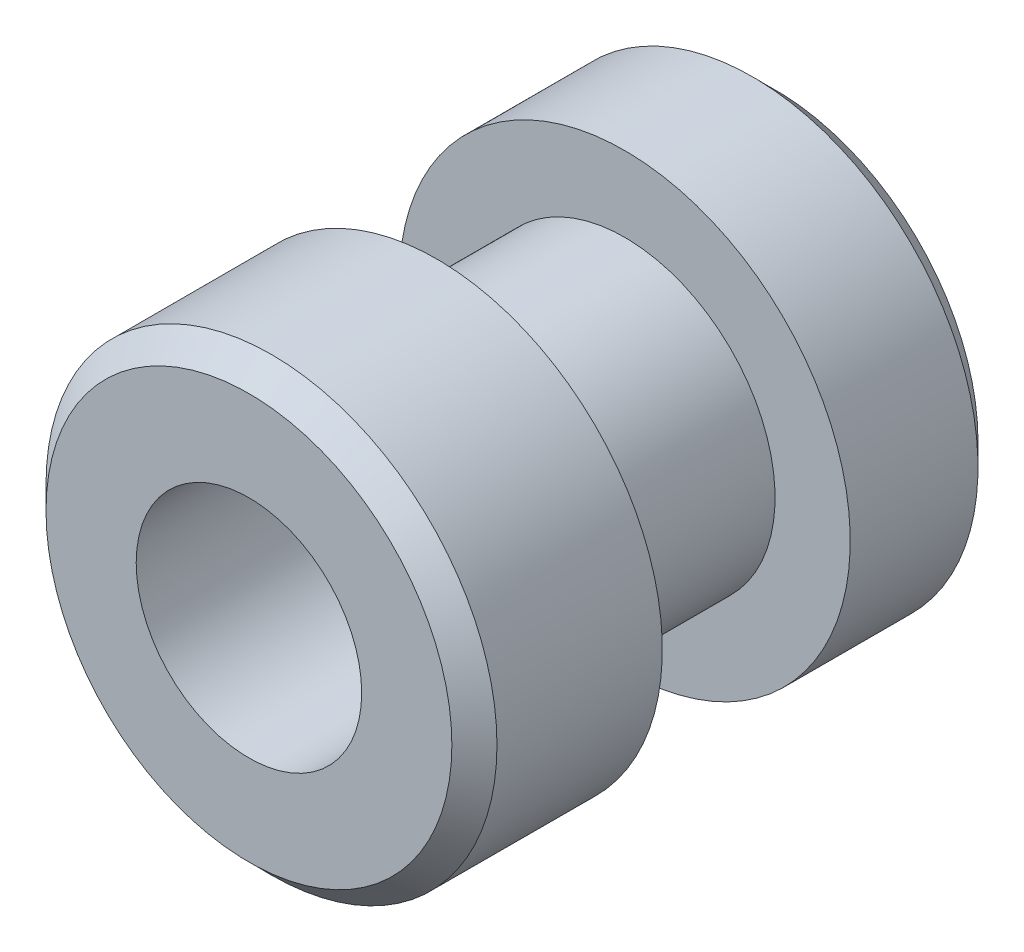
SolidWorks part; units mm, degrees
material "硅橡胶"
ref_plane "前视基准面" through (0, 0, 0) normal (0, 0, 1) x (1, 0, 0)
ref_plane "上视基准面" through (0, 0, 0) normal (0, 1, 0) x (1, 0, 0)
ref_plane "右视基准面" through (0, 0, 0) normal (1, 0, 0) x (0, 0, -1)
sketch "草图2" plane through (0, 0, 0) normal (0, 1, 0) x (1, 0, 0)
  line L0 (0, 2.413) -> (0, 0) construction
  line L1 (-1.5, 7) -> (-3, 7)
  line L2 (-3, 7) -> (-3, 5)
  line L3 (-3, 5) -> (-2, 5)
  line L4 (-2, 5) -> (-2, 2.5)
  line L5 (-2, 2.5) -> (-3, 2.5)
  line L6 (-3, 2.5) -> (-3, 0)
  line L7 (-3, 0) -> (-1.5, 0)
  line L8 (-1.5, 7) -> (-1.5, 0)
  point P12 (-3, 6)
  dimension "D1" = 3
  dimension "D2" = 6
  dimension "D3" = 4
  dimension "D4" = 2.5
  dimension "D5" = 2.5
  dimension "D6" = 2
revolve "旋转1" add sketch "草图2" angle 360 about L0
chamfer "倒角1" distance 0.3 angle 45 2 edges at (-3, 0, 0) (-3, 0, -7)
